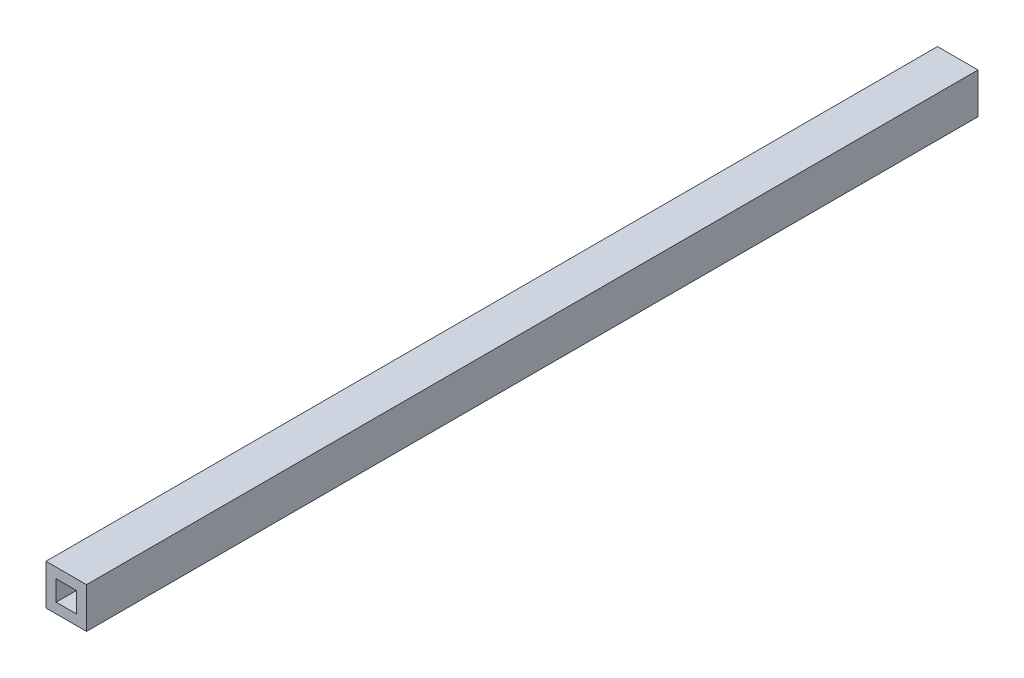
SolidWorks part; units mm, degrees
material "6063-O"
ref_plane "Front Plane" through (0, 0, 0) normal (0, 0, 1) x (1, 0, 0)
ref_plane "Top Plane" through (0, 0, 0) normal (0, 1, 0) x (1, 0, 0)
ref_plane "Right Plane" through (0, 0, 0) normal (1, 0, 0) x (0, 0, -1)
sketch "Sketch1" plane through (0, 0, 0) normal (0, 0, 1) x (1, 0, 0)
  line L1 (-10, -10) -> (10, -10)
  line L2 (-10, -10) -> (-10, 10)
  line L3 (-10, 10) -> (10, 10)
  line L4 (10, -10) -> (10, 10)
  line L5 (-10, -10) -> (10, 10) construction
  line L6 (-10, 10) -> (10, -10) construction
  point P0 (0, 0)
  dimension "D1" = 20
extrude "Extrude-Thin1" add sketch "Sketch1" along normal blind 440 thin thin type one direction reverse wall 5
